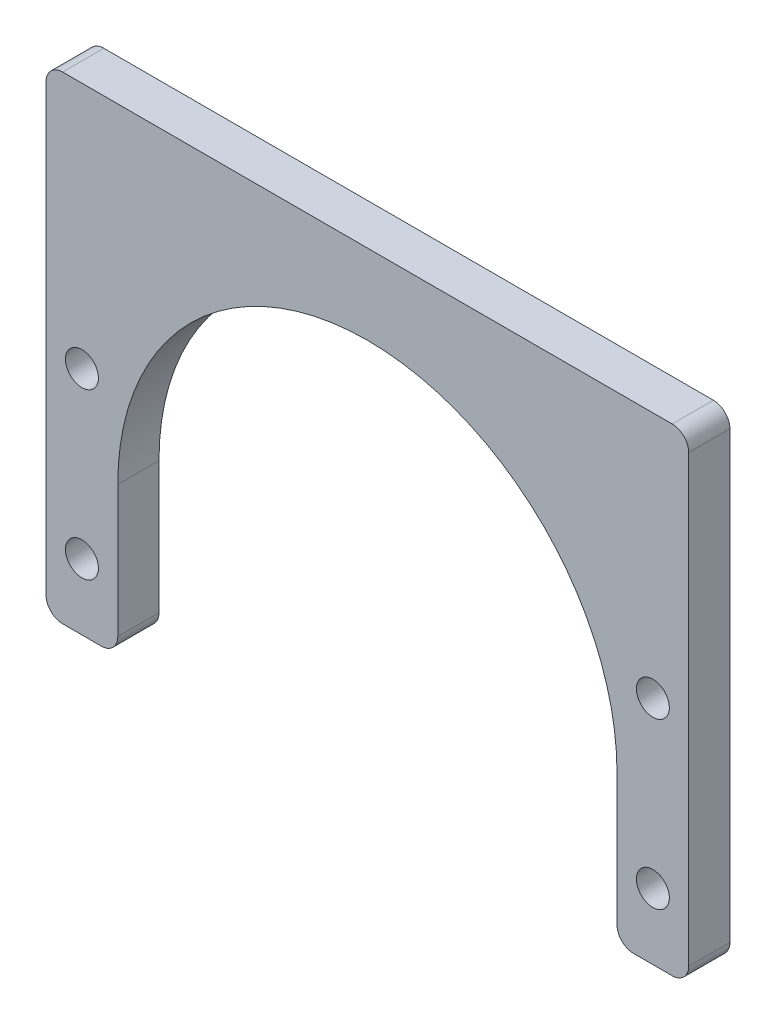
SolidWorks part; units mm, degrees
ref_plane "前视基准面" through (0, 0, 0) normal (0, 0, 1) x (1, 0, 0)
ref_plane "上视基准面" through (0, 0, 0) normal (0, 1, 0) x (1, 0, 0)
ref_plane "右视基准面" through (0, 0, 0) normal (1, 0, 0) x (0, 0, -1)
sketch "草图1" plane through (0, 0, 0) normal (0, 0, 1) x (1, 0, 0)
  line L0 (0, 60.5413) -> (0, -56.4587) construction
  line L1 (-39, 40) -> (39, 40)
  line L2 (-39, 0) -> (-30.3, 0)
  line L3 (-39, 40) -> (-39, -18)
  line L4 (-30.3, 0) -> (-30.3, -18)
  line L5 (-30.3, -18) -> (-39, -18)
  line L6 (-34.65, -18) -> (-34.65, 17.9881) construction
  line L7 (39, 40) -> (39, -18)
  line L8 (30.3, -18) -> (39, -18)
  line L9 (30.3, 0) -> (30.3, -18)
  line L10 (30.3, 0) -> (39, 0)
  arc A0 (30.3, 0) -> (-30.3, 0) centre (0, 0) ccw
  circle A1 centre (-34.65, 10) radius 2
  circle A2 centre (-34.65, -10) radius 2
  circle A3 centre (34.65, -10) radius 2
  circle A4 centre (34.65, 10) radius 2
  point P7 (0, 40)
  dimension "D1" = 78
  dimension "D2" = 60.6
  dimension "D3" = 20
  dimension "D4" = 40
  dimension "D5" = 8
extrude "凸台-拉伸1" add sketch "草图1" along normal blind 5 contours A0 L10 L7 L1 L3 L2 A1 A4 | L5 L4 L2 L3 A2 | L10 L9 L8 L7 A3
fillet "圆角1" radius 2 6 edges at (-30.3, -18, 2.5) (-39, -18, 2.5) (30.3, -18, 2.5) (39, -18, 2.5) (39, 40, 2.5) (-39, 40, 2.5)
